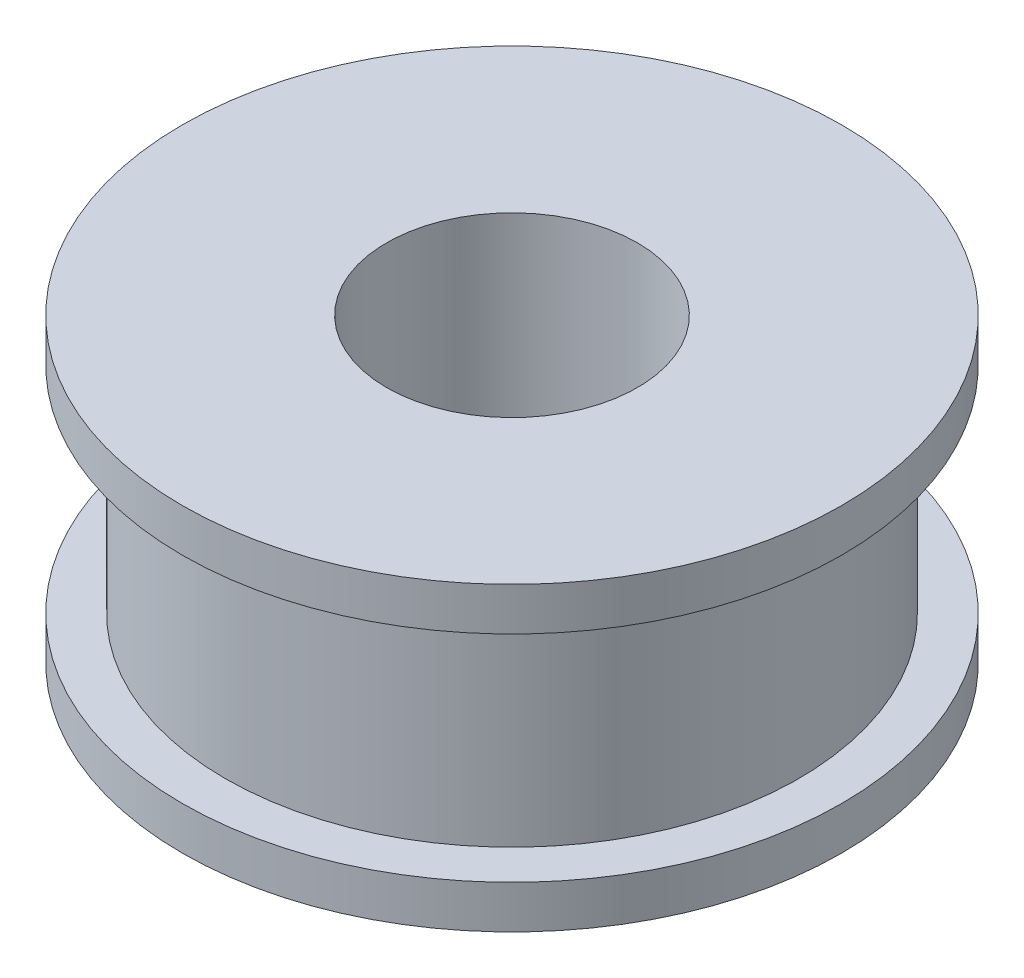
SolidWorks part; units mm, degrees
ref_plane "前视基准面" through (0, 0, 0) normal (0, 0, 1) x (1, 0, 0)
ref_plane "上视基准面" through (0, 0, 0) normal (0, 1, 0) x (1, 0, 0)
ref_plane "右视基准面" through (0, 0, 0) normal (1, 0, 0) x (0, 0, -1)
other "Configuration Table"
sketch "草图1" plane through (0, 0, 0) normal (0, 1, 0) x (1, 0, 0)
  circle A0 centre (0, 0) radius 4
  dimension "D1" = 8
extrude "凸台-拉伸1" add sketch "草图1" along normal blind 3
sketch "草图3" plane through (0, 3, 0) normal (0, 1, 0) x (1, 0, 0)
  circle A0 centre (0, 0) radius 4.6
  dimension "D1" = 9.2
extrude "凸台-拉伸2" add sketch "草图3" along normal blind 0.6
sketch "草图4" plane through (0, 0, 0) normal (0, -1, 0) x (1, 0, 0)
  circle A0 centre (0, 0) radius 4.6 construction
  circle A1 centre (0, 0) radius 4.6
extrude "凸台-拉伸3" add sketch "草图4" along normal blind 0.6
sketch "草图5" plane through (0, -0.6, 0) normal (0, -1, 0) x (1, 0, 0)
  circle A0 centre (0, 0) radius 1.75
  dimension "D1" = 3.5
extrude "切除-拉伸1" cut sketch "草图5" against normal blind 11
